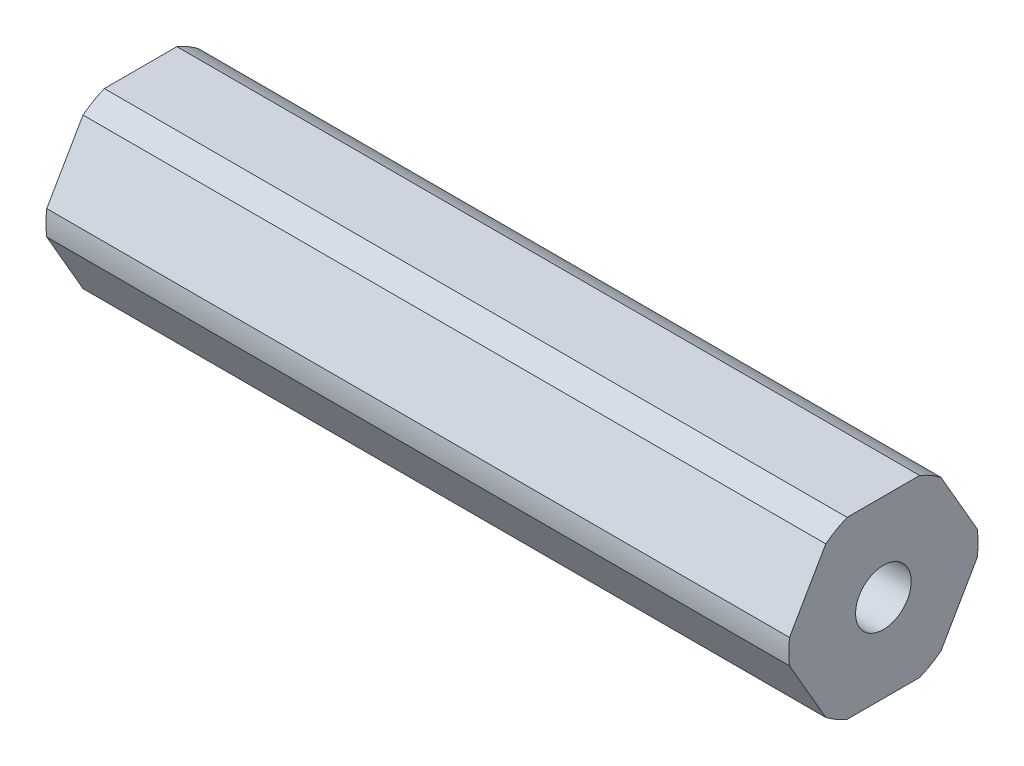
SolidWorks part; units mm, degrees
material "6061-T6 (SS)"
ref_plane "Front Plane" through (0, 0, 0) normal (0, 0, 1) x (1, 0, 0)
ref_plane "Top Plane" through (0, 0, 0) normal (0, 1, 0) x (1, 0, 0)
ref_plane "Right Plane" through (0, 0, 0) normal (1, 0, 0) x (0, 0, -1)
sketch "Sketch1" plane through (0, 0, 0) normal (1, 0, 0) x (0, 0, -1)
  line L1 (7.3323, 0) -> (3.6662, 6.35)
  line L2 (3.6662, 6.35) -> (-3.6662, 6.35)
  line L3 (-3.6662, 6.35) -> (-7.3323, 0)
  line L4 (-7.3323, 0) -> (-3.6662, -6.35)
  line L5 (-3.6662, -6.35) -> (3.6662, -6.35)
  line L6 (3.6662, -6.35) -> (7.3323, 0)
  circle A0 centre (0, 0) radius 6.35 construction
  circle A1 centre (0, 0) radius 6.875
  circle A2 centre (0, 0) radius 2.0193
  dimension "D1" = 12.7
  dimension "D2" = 13.75
  dimension "D3" = 4.0386
extrude "Boss-Extrude1" add sketch "Sketch1" along normal mid plane 53.9242 contours L1 A1 L2 L3 L4 L5 L6 A2
equation "\"D2@Sketch1\"=13.75MM"
equation "\"D3@Sketch1\"=.159"
